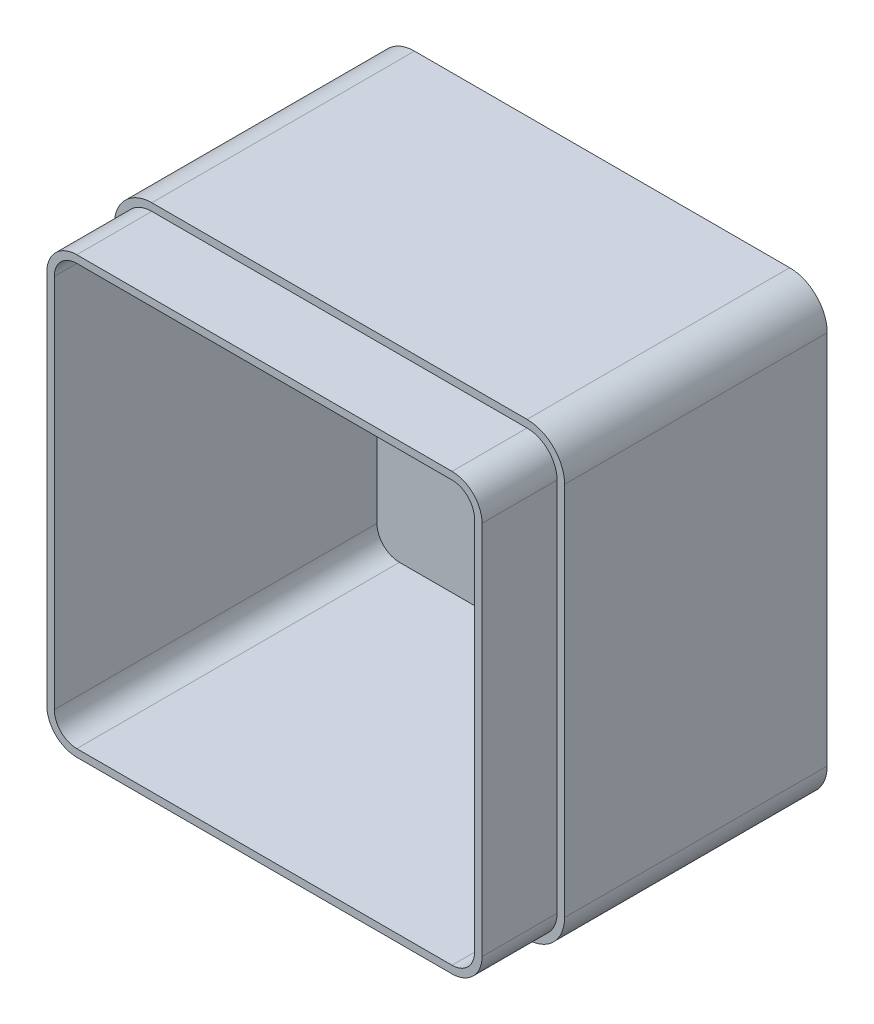
SolidWorks part; units mm, degrees
ref_plane "Front Plane" through (0, 0, 0) normal (0, 0, 1) x (1, 0, 0)
ref_plane "Top Plane" through (0, 0, 0) normal (0, 1, 0) x (1, 0, 0)
ref_plane "Right Plane" through (0, 0, 0) normal (1, 0, 0) x (0, 0, -1)
sketch "Sketch1" plane through (0, 0, 0) normal (0, 0, 1) x (1, 0, 0)
  line L1 (0, 0) -> (120, 0)
  line L2 (0, 0) -> (0, 120)
  line L3 (0, 120) -> (120, 120)
  line L4 (120, 0) -> (120, 120)
  dimension "D1" = 120
  dimension "D2" = 120
extrude "Boss-Extrude1" add sketch "Sketch1" along normal blind 90
fillet "Fillet1" radius 10 4 edges at (0, 0, 45) (120, 120, 45) (120, 0, 45) (0, 120, 45)
shell "Shell1" thickness 4
sketch "Sketch2" plane through (0, 0, 90) normal (0, 0, 1) x (1, 0, 0)
  line L8 (2, 110) -> (2, 10)
  line L9 (10, 2) -> (110, 2)
  line L10 (118, 10) -> (118, 110)
  line L11 (110, 118) -> (10, 118)
  line L12 (2, 110) -> (2, 10)
  line L13 (10, 2) -> (110, 2)
  line L14 (118, 10) -> (118, 110)
  line L15 (110, 118) -> (10, 118)
  arc A8 (2, 10) -> (10, 2) centre (10, 10) ccw
  arc A9 (110, 2) -> (118, 10) centre (110, 10) ccw
  arc A10 (118, 110) -> (110, 118) centre (110, 110) ccw
  arc A11 (10, 118) -> (2, 110) centre (10, 110) ccw
  arc A12 (2, 10) -> (10, 2) centre (10, 10) ccw
  arc A13 (110, 2) -> (118, 10) centre (110, 10) ccw
  arc A14 (118, 110) -> (110, 118) centre (110, 110) ccw
  arc A15 (10, 118) -> (2, 110) centre (10, 110) ccw
  dimension "D1" = 2
extrude "Cut-Extrude1" cut sketch "Sketch2" against normal blind 20 flip side to cut
